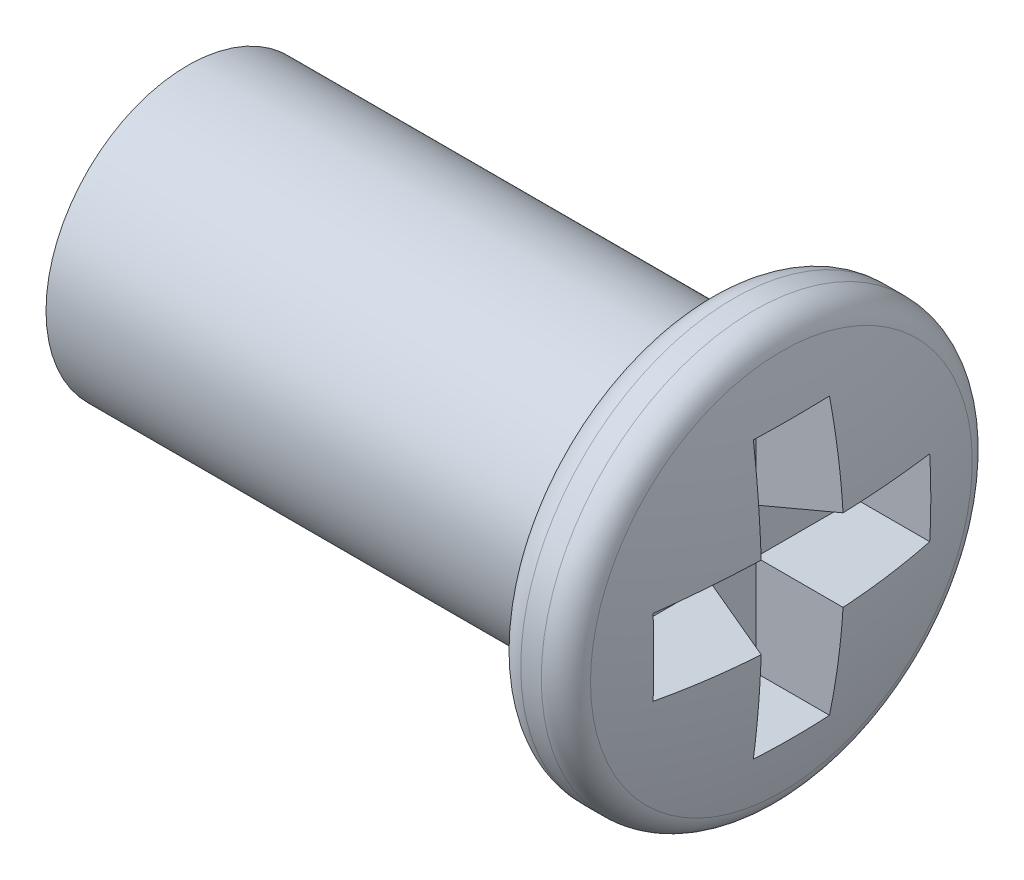
SolidWorks part; units mm, degrees
ref_plane "Front Plane" through (0, 0, 0) normal (0, 0, 1) x (1, 0, 0)
ref_plane "Top Plane" through (0, 0, 0) normal (0, 1, 0) x (1, 0, 0)
ref_plane "Right Plane" through (0, 0, 0) normal (1, 0, 0) x (0, 0, -1)
sketch "Sketch1" plane through (0, 0, 0) normal (0, 0, 1) x (1, 0, 0)
  line L0 (0, 0) -> (4.35, 0)
  line L1 (4.15, 1.5) -> (3.65, 1.5)
  line L2 (3.65, 1.5) -> (3.65, 1)
  line L3 (3.65, 1) -> (0, 1)
  line L4 (0, 1) -> (0, 0)
  line L5 (-102.0382, 0) -> (4999.8703, 0) construction
  arc A0 (4.35, 0) -> (4.15, 1.5) centre (-1.375, 0) ccw
  dimension "D1" = 2
  dimension "D2" = 0.7
  dimension "D3" = 4.35
  dimension "D4" = 3
  dimension "D5" = 0.5
revolve "Revolve1" add sketch "Sketch1" angle 360 about L5
fillet "Fillet1" radius 0.2 2 edges at (3.65, 0, 1.5) (4.15, 0, 1.5)
ref_plane "Plane1" through (4.35, 0, 0) normal (1, 0, 0) x (0, 0, -1)
sketch "Sketch2" plane through (4.35, 0, 0) normal (1, 0, 0) x (0, 0, -1)
  line L1 (0.2927, 1) -> (0.2927, 0.2927)
  line L2 (0.2927, 0.2927) -> (1, 0.2927)
  line L3 (1, 0.2927) -> (1, -0.2927)
  line L4 (1, -0.2927) -> (0.2927, -0.2927)
  line L5 (0.2927, -0.2927) -> (0.2927, -1)
  line L6 (0.2927, -1) -> (-0.2927, -1)
  line L7 (-0.2927, -1) -> (-0.2927, -0.2927)
  line L8 (-0.2927, -0.2927) -> (-1, -0.2927)
  line L9 (-1, -0.2927) -> (-1, 0.2927)
  line L10 (-1, 0.2927) -> (-0.2927, 0.2927)
  line L11 (-0.2927, 0.2927) -> (-0.2927, 1)
  line L12 (-0.2927, 1) -> (0.2927, 1)
  point P0 (0, 1)
  point P1 (1, 0)
  dimension "D1" = 2
extrude "Cut-Extrude1" cut sketch "Sketch2" against normal blind 0.5 draft 15
